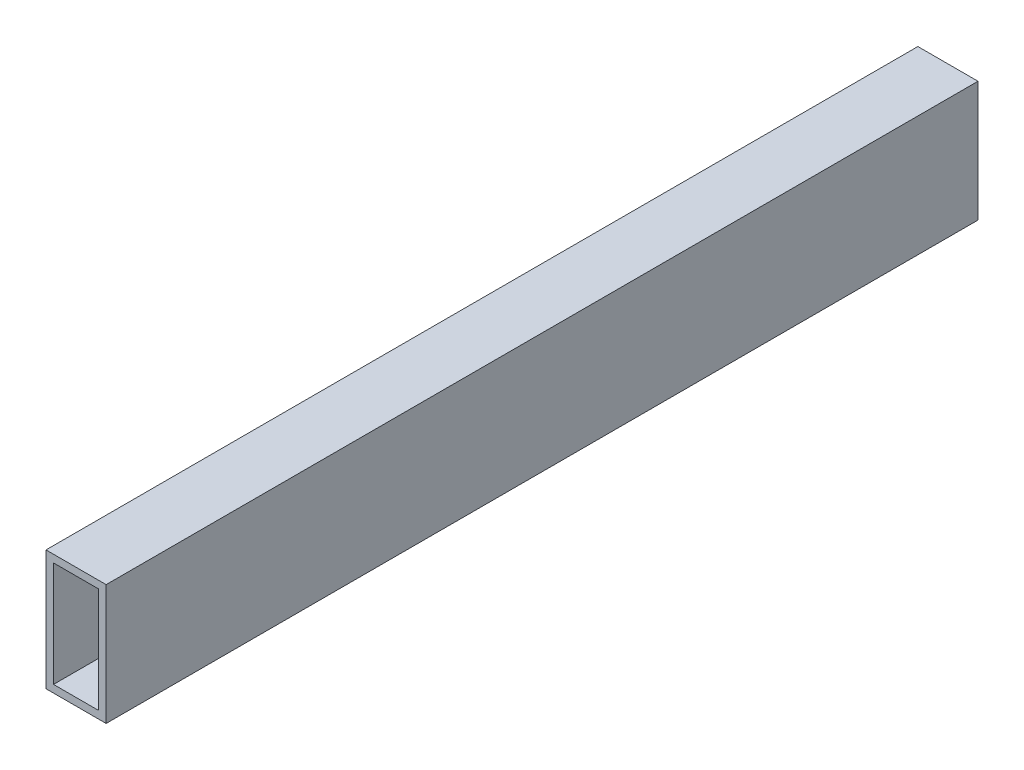
SolidWorks part; units mm, degrees
material "6061-T6 (SS)"
ref_plane "Front Plane" through (0, 0, 0) normal (0, 0, 1) x (1, 0, 0)
ref_plane "Top Plane" through (0, 0, 0) normal (0, 1, 0) x (1, 0, 0)
ref_plane "Right Plane" through (0, 0, 0) normal (1, 0, 0) x (0, 0, -1)
sketch "Sketch2" plane through (0, 0, 0) normal (0, 0, 1) x (1, 0, 0)
  line L0 (-9.525, 22.225) -> (9.525, 22.225)
  line L1 (-12.7, 25.4) -> (12.7, 25.4)
  line L2 (-12.7, 25.4) -> (-12.7, -25.4)
  line L3 (-12.7, -25.4) -> (12.7, -25.4)
  line L4 (12.7, 25.4) -> (12.7, -25.4)
  line L5 (-12.7, 25.4) -> (12.7, -25.4) construction
  line L6 (-12.7, -25.4) -> (12.7, 25.4) construction
  line L7 (9.525, 22.225) -> (9.525, -22.225)
  line L8 (-9.525, -22.225) -> (9.525, -22.225)
  line L9 (-9.525, 22.225) -> (-9.525, -22.225)
  point P0 (0, 0)
  dimension "D1" = 50.8
  dimension "D2" = 25.4
  dimension "D3" = 3.175
extrude "Boss-Extrude1" add sketch "Sketch2" along normal mid plane 368.3
